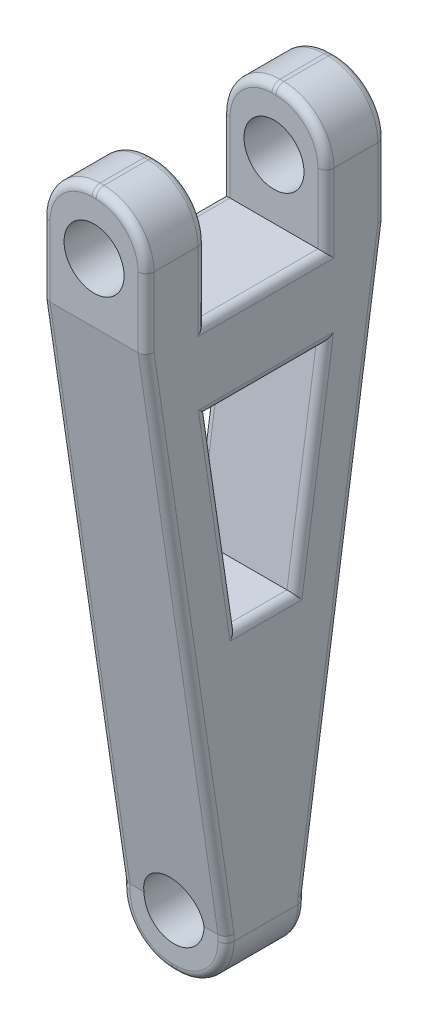
SolidWorks part; units mm, degrees
ref_plane "Front Plane" through (0, 0, 0) normal (1, 0, 0) x (0, 1, 0)
ref_plane "Top Plane" through (0, 0, 0) normal (0, 0, 1) x (0, 1, 0)
ref_plane "Right Plane" through (0, 0, 0) normal (0, 1, 0) x (-1, 0, 0)
sketch "Sketch1" plane through (0, 0, 0) normal (1, 0, 0) x (0, 1, 0)
  line L0 (0, 0) -> (-108.5399, 0) construction
  line L1 (-108.5399, 0) -> (95.7766, 0) construction
  line L2 (-54.27, -10) -> (-54.27, 10)
  line L3 (-54.27, 10) -> (-40.299, 10)
  line L4 (-40.299, 10) -> (95.73, 30)
  line L5 (95.73, 30) -> (125.73, 30)
  line L6 (125.73, 30) -> (125.73, 15)
  line L7 (125.73, 15) -> (95.73, 15)
  line L8 (95.73, 15) -> (95.73, -15)
  line L9 (25.73, -7.2477) -> (25.73, 7.2477)
  line L10 (25.73, 7.2477) -> (75.73, 14.5991)
  line L11 (75.73, 14.5991) -> (75.73, -14.5991)
  line L12 (25.73, -7.2477) -> (75.73, -14.5991)
  line L13 (125.73, -15) -> (95.73, -15)
  line L14 (125.73, -30) -> (125.73, -15)
  line L15 (95.73, -30) -> (125.73, -30)
  line L16 (-40.299, -10) -> (95.73, -30)
  line L17 (-54.27, -10) -> (-40.299, -10)
  point P17 (25.73, 0)
  point P18 (75.73, 0)
  point P19 (95.73, 0)
  point P24 (-54.27, 0)
  dimension "D1" = 10
  dimension "D2" = 30
  dimension "D3" = 15
  dimension "D4" = 180
  dimension "D5" = 30
  dimension "D6" = 30
  dimension "D7" = 20
  dimension "D8" = 70
extrude "Boss-Extrude1" add sketch "Sketch1" against normal blind 1 and the other way blind 25 contours L9 L10 L11 L12 | L8 L13 L14 L15 L16 L17 L2 L3 L4 L5 L6 L7
fillet "Fillet1" radius 12.5 6 edges at (-1, -54.27, 0) (25, -54.27, 0) (-1, 125.73, -22.5) (25, 125.73, -22.5) (-1, 125.73, 22.5) (25, 125.73, 22.5)
sketch "Sketch3" plane through (0, 0, 0) normal (0, 0, 1) x (0, 1, 0)
  line L0 (-40.299, -25) -> (-40.299, 1) construction
  circle A0 centre (-40.299, -12) radius 7.5
  circle A1 centre (110.6195, -12) radius 7.5
  dimension "D1" = 15
  dimension "D2" = 15
extrude "Cut-Extrude3" cut sketch "Sketch3" against normal through all both and the other way through all contours A0 | A1
fillet "Fillet4" radius 2 44 edges at (12, 125.73, -15) (12, 125.73, 15) (12, 125.73, -30) (25, -41.0345, -10) (-1, -41.0345, -10) (12, -54.27, -10) (12, 125.73, 30) (-1, -41.0345, 10) (12, -54.27, 10) (25, -41.0345, 10) (-1, 104.48, -15) (2.6612, 122.0689, -15) (21.3388, 122.0689, -15) (25, 104.48, -15) (25, 95.73, 0) (-1, 95.73, 0) (-1, 104.48, 15) (25, 104.48, 15) (21.3388, 122.0689, 15) (2.6612, 122.0689, 15) (-1, 50.73, -10.9234) (-1, 25.73, 0) (-1, 50.73, 10.9234) (-1, 75.73, 0) (25, 104.48, -30) (21.3388, 122.0689, -30) (2.6612, 122.0689, -30) (-1, 104.48, -30) (-1, 27.7155, -20) (2.6612, -50.6088, -10) (21.3388, -50.6088, -10) (25, 27.7155, -20) (25, 50.73, -10.9234) (25, 25.73, 0) (25, 50.73, 10.9234) (25, 75.73, 0) (25, 104.48, 30) (21.3388, 122.0689, 30) (2.6612, 122.0689, 30) (-1, 104.48, 30) (-1, 27.7155, 20) (2.6612, -50.6088, 10) (21.3388, -50.6088, 10) (25, 27.7155, 20)
